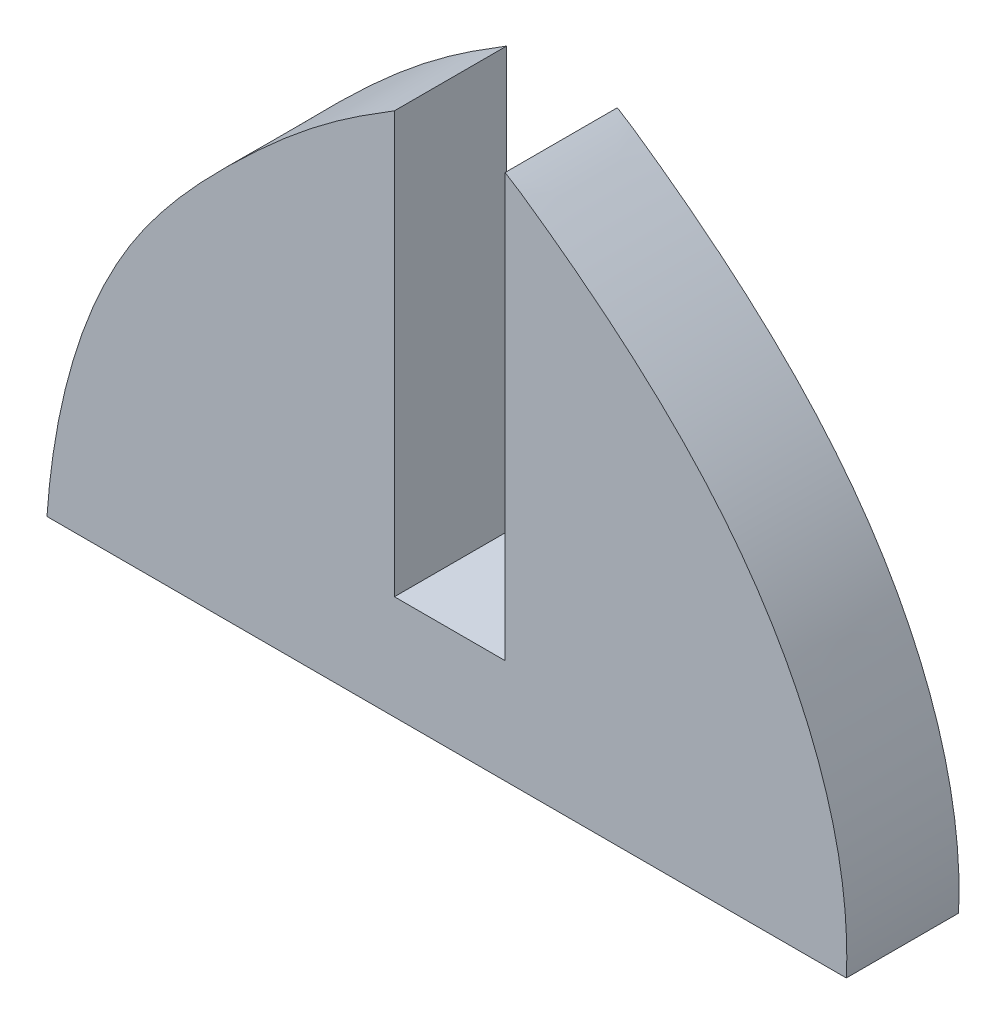
SolidWorks part; units mm, degrees
ref_plane "前视基准面" through (0, 0, 0) normal (0, 0, 1) x (1, 0, 0)
ref_plane "上视基准面" through (0, 0, 0) normal (0, 1, 0) x (1, 0, 0)
ref_plane "右视基准面" through (0, 0, 0) normal (1, 0, 0) x (0, 0, -1)
other "Configuration Table"
sketch "草图1" plane through (0, 0, 0) normal (0, 0, 1) x (1, 0, 0)
  line L0 (157.4101, 256.0211) -> (779.9201, 256.0211) construction
  line L1 (227.8199, 597.9035) -> (1733.8199, 597.9035) construction
  line L2 (376.5, 617) -> (1882.5, 617) construction
  line L6 (1180.2326, 162.9506) -> (1237.2119, 162.9506)
  line L7 (1208.8887, 170.3804) -> (1208.8887, 150.2319) construction
  line L8 (1205.0003, 200.3804) -> (1205.0003, 170.3804)
  line L11 (1205.0003, 171.7054) -> (1205.0003, 200.3804)
  line L13 (1205.0003, 170.3804) -> (1212.8887, 170.3804)
  line L14 (1212.8887, 170.3804) -> (1212.8887, 200.5148)
  spline S0 degree 3 poles (1212.8887, 200.5148) (1213.5918, 200.1027) (1216.3222, 198.2066) (1221.9149, 193.9644) (1232.596, 183.6254) (1237.638, 171.4915) (1237.2119, 162.9506) knots 0.03839 0.03839 0.03839 0.03839 0.088764 0.237953 0.477618 1 1 1 1
  spline S1 degree 3 poles (1205.0003, 200.3804) (1203.8021, 199.6441) (1199.6594, 197.0296) (1193.2768, 191.4389) (1183.5241, 180.8663) (1180.6944, 169.8063) (1180.2326, 162.9506) knots 0.038951 0.038951 0.038951 0.038951 0.12574 0.329523 0.570719 1 1 1 1
  dimension "D1" = 30.1344
extrude "凸台-拉伸1" add sketch "草图1" along normal blind 8 contours L8 S1 L6 S0 L14 L13
